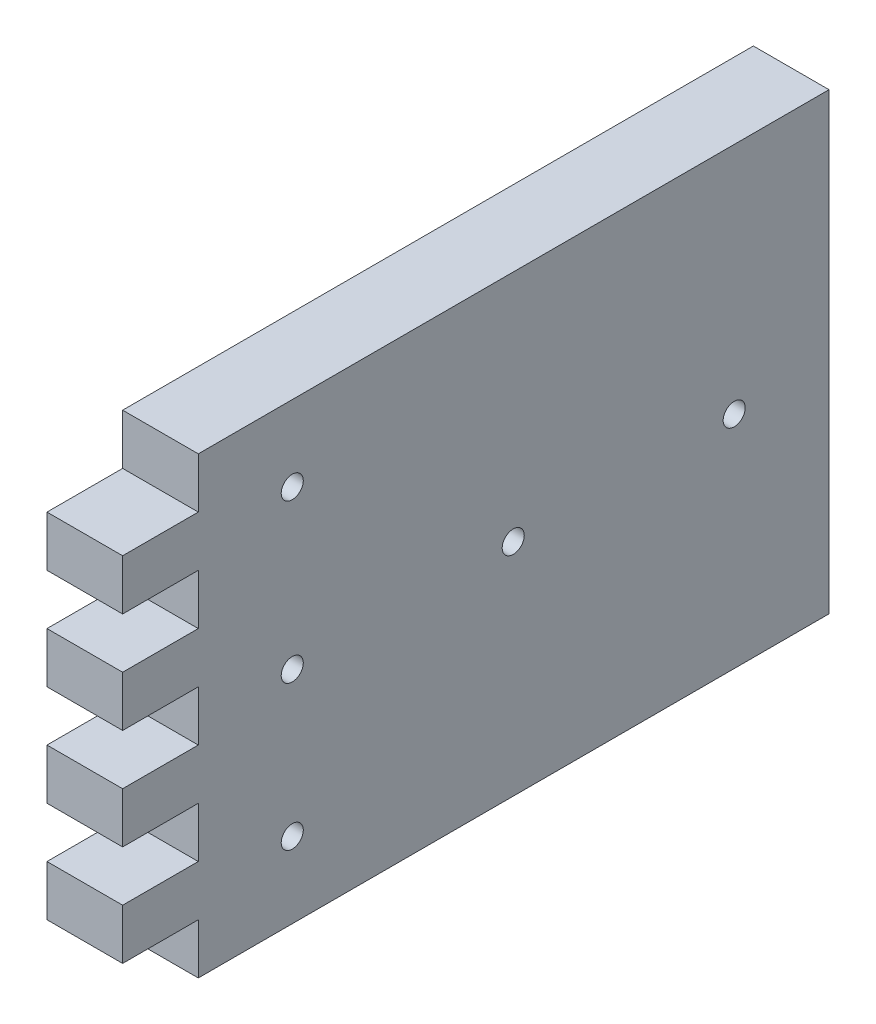
SolidWorks part; units mm, degrees
material "Pine"
ref_plane "Front Plane" through (0, 0, 0) normal (0, 0, 1) x (1, 0, 0)
ref_plane "Top Plane" through (0, 0, 0) normal (0, 1, 0) x (1, 0, 0)
ref_plane "Right Plane" through (0, 0, 0) normal (1, 0, 0) x (0, 0, -1)
sketch "Sketch1" plane through (0, 0, 0) normal (1, 0, 0) x (0, 0, -1)
  line L0 (19.05, 101.6) -> (19.05, 88.9) construction
  line L1 (19.05, 0) -> (177.8635, 0)
  line L2 (0, 12.7) -> (0, 25.4)
  line L3 (19.05, 114.3) -> (177.8635, 114.3)
  line L5 (177.8635, 114.3) -> (177.8635, 0)
  line L13 (0, 101.6) -> (19.05, 101.6)
  line L14 (19.05, 114.3) -> (19.05, 101.6)
  line L17 (0, 88.9) -> (19.05, 88.9)
  line L19 (0, 76.2) -> (19.05, 76.2)
  line L20 (19.05, 88.9) -> (19.05, 76.2)
  line L21 (0, 88.9) -> (19.05, 76.2) construction
  line L22 (0, 76.2) -> (19.05, 88.9) construction
  line L23 (0, 63.5) -> (19.05, 63.5)
  line L25 (0, 50.8) -> (19.05, 50.8)
  line L26 (19.05, 63.5) -> (19.05, 50.8)
  line L27 (0, 63.5) -> (19.05, 50.8) construction
  line L28 (0, 50.8) -> (19.05, 63.5) construction
  line L29 (0, 38.1) -> (19.05, 38.1)
  line L31 (0, 25.4) -> (19.05, 25.4)
  line L32 (19.05, 38.1) -> (19.05, 25.4)
  line L33 (0, 38.1) -> (19.05, 25.4) construction
  line L34 (0, 25.4) -> (19.05, 38.1) construction
  line L37 (0, 12.7) -> (19.05, 12.7)
  line L38 (19.05, 0) -> (19.05, 12.7)
  line L41 (19.05, 76.2) -> (19.05, 63.5) construction
  line L42 (19.05, 50.8) -> (19.05, 38.1) construction
  line L43 (19.05, 25.4) -> (19.05, 12.7) construction
  line L44 (0, 88.9) -> (0, 101.6)
  line L45 (0, 63.5) -> (0, 76.2)
  line L46 (0, 38.1) -> (0, 50.8)
  point P4 (177.8635, 55.88)
  point P14 (9.525, 82.55)
  point P19 (9.525, 57.15)
  point P24 (9.525, 31.75)
  dimension "D1" = 114.3
  dimension "D2" = 158.8135
  dimension "D3" = 12.7
  dimension "D4" = 19.05
extrude "Boss-Extrude1" add sketch "Sketch1" along normal blind 19.05
hole_wizard "7/32 (0.21875) Diameter Hole3" positions "Sketch3" profile "Sketch4" hole size "7/32" standard "ANSI Inch" end condition up to next
sketch "Sketch3" plane through (19.05, 0, 0) normal (1, 0, 0) x (0, 0, -1)
  line L1 (177.8635, 55.499) -> (153.9875, 55.499) construction
  line L2 (177.8635, 0) -> (177.8635, 114.3) construction
  line L3 (153.9875, 55.499) -> (98.3488, 55.499) construction
  line L4 (98.3488, 55.499) -> (42.7101, 55.499) construction
  line L5 (19.05, 0) -> (177.8635, 0) construction
  line L6 (42.7101, 114.3) -> (42.7101, 95.25) construction
  line L7 (177.8635, 114.3) -> (19.05, 114.3) construction
  line L8 (42.7101, 95.25) -> (42.7101, 55.499) construction
  line L9 (42.7101, 55.499) -> (42.7101, 19.05) construction
  line L10 (42.7101, 19.05) -> (42.7101, 0) construction
  point P10 (153.9875, 55.499)
  point P14 (98.3488, 55.499)
  point P16 (42.7101, 55.499)
  point P39 (42.7101, 95.25)
  point P42 (42.7101, 19.05)
  dimension "D1" = 23.876
  dimension "D2" = 55.6387
  dimension "D3" = 55.499
  dimension "D4" = 19.05
sketch "Sketch4" plane through (19.05, 19.05, -42.7101) normal (0, 1, 0) x (0, 0, -1)
  line L0 (0, 0) -> (0, 19.05)
  line L1 (0, 19.05) -> (2.7781, 19.05)
  line L2 (2.7781, 19.05) -> (2.7781, 0)
  line L5 (2.7781, 0) -> (0, 0)
  line L11 (0, -6.35) -> (0, 107.95) construction
  dimension "Thru Hole Dia." = 5.5562
  dimension "Thru Hole Depth" = 19.05
